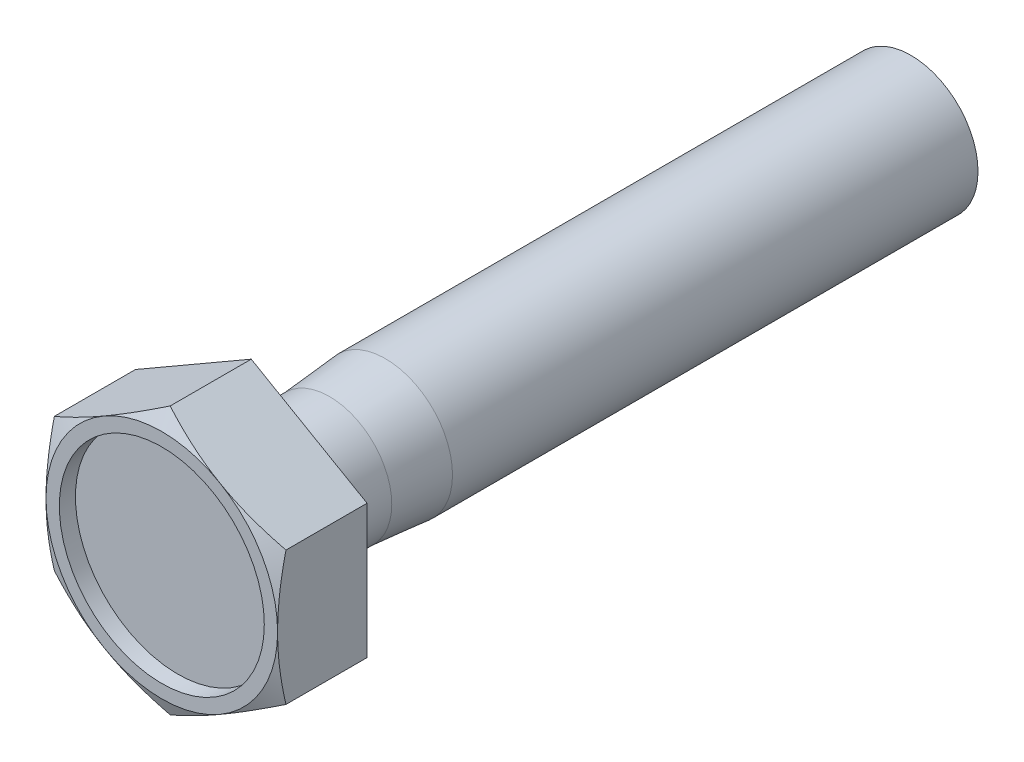
SolidWorks part; units mm, degrees
extrude "基体-拉伸" add sketch "草图3" along normal blind 2
sketch "草图3" plane through (0, 0, 0) normal (0, 0, 1) x (1, 0, 0)
  line L1 (2.5894, -1.495) -> (2.5894, 1.495)
  line L2 (2.5894, 1.495) -> (0, 2.99)
  line L3 (0, 2.99) -> (-2.5894, 1.495)
  line L4 (-2.5894, 1.495) -> (-2.5894, -1.495)
  line L5 (-2.5894, -1.495) -> (0, -2.99)
  line L6 (0, -2.99) -> (2.5894, -1.495)
  circle A0 centre (0, 0) radius 2.5894 construction
  dimension "D1" = 5.98
revolve "凸台-旋转1" add sketch "草图6"
sketch "草图6" plane through (0, 0, 0) normal (1, 0, 0) x (0, 0, -1)
  line L0 (0, 0) -> (2.3184, 0) construction
  line L2 (0, 1.3917) -> (1.75, 1.3917)
  line L3 (0, -1.495) -> (0, 1.495) construction
  line L4 (1.75, 1.3917) -> (3, 1.5)
  line L5 (3, 1.5) -> (15, 1.5)
  line L6 (15, 1.5) -> (15, 0)
  line L7 (0, 0) -> (15, 0)
  line L8 (0, 0) -> (0, 1.3917)
  dimension "D1" = 2.7835
  dimension "D2" = 3
  dimension "D3" = 1.25
  dimension "D4" = 15
  dimension "D5" = 12
cosmetic thread "螺旋线1"
revolve "切除-旋转1" cut sketch "草图7" angle 360 about L5
sketch "草图7" plane through (0, 0, 0) normal (0, 1, 0) x (1, 0, 0)
  line L0 (1.5, 15.25) -> (1.5, 14.75)
  line L1 (1.5, 14.75) -> (1.067, 15)
  line L2 (1.5, 15) -> (-1.5, 15) construction
  line L3 (1.067, 15) -> (1.5, 15.25)
  line L5 (0, 0) -> (0, 2.1791) construction
  dimension "D2" = 60
  dimension "D3" = 60
  dimension "D1" = 0.433
  dimension "D4" = 1.5
material "5.8级"
ref_plane "前视" through (0, 0, 0) normal (0, 0, 1) x (1, 0, 0)
ref_plane "上视" through (0, 0, 0) normal (0, 1, 0) x (1, 0, 0)
ref_plane "右视" through (0, 0, 0) normal (1, 0, 0) x (0, 0, -1)
sketch "尺寸草图" plane through (0, 0, 0) normal (0, 1, 0) x (1, 0, 0)
  line L0 (4.2057, 0) -> (-4.2057, 0)
  line L1 (30.1422, -1.495) -> (30.1422, 1.495)
  line L2 (30.1422, 1.495) -> (27.5527, 2.99)
  line L3 (27.5527, 2.99) -> (24.9633, 1.495)
  line L4 (24.9633, 1.495) -> (24.9633, -1.495)
  line L5 (24.9633, -1.495) -> (27.5527, -2.99)
  line L6 (27.5527, -2.99) -> (30.1422, -1.495)
  line L7 (-4.2057, 0) -> (-5.2005, 0.6605)
  line L8 (-5.2005, 0.6605) -> (-5.2005, 2)
  line L9 (-5.2005, 2) -> (-0.945, 2)
  line L10 (-0.845, 2.1) -> (-0.845, 3.75)
  line L11 (-0.845, 3.75) -> (-1.5, 5)
  line L12 (-1.5, 5) -> (-1.5, 17)
  line L13 (-1.5, 17) -> (1.5, 17)
  line L14 (1.5, 5) -> (1.5, 17)
  line L15 (0, 0) -> (0, -2.324) construction
  line L16 (0.845, 3.75) -> (1.5, 5)
  line L17 (0.845, 2.1) -> (0.845, 3.75)
  line L18 (5.2005, 2) -> (0.945, 2)
  line L19 (5.2005, 0.6605) -> (5.2005, 2)
  line L20 (4.2057, 0) -> (5.2005, 0.6605)
  circle A0 centre (27.5527, 0) radius 2.5894 construction
  circle A1 centre (27.5527, 0) radius 2.75
  arc A2 (-0.945, 2) -> (-0.845, 2.1) centre (-0.945, 2.1) ccw
  arc A3 (0.945, 2) -> (0.845, 2.1) centre (0.945, 2.1) cw
  point P26 (1.5, 17)
  point P31 (1.5, 16.5)
  point P32 (0, 12)
  dimension "s" = 5.5
sketch "草图4" plane through (0, 0, 2) normal (0, 0, 1) x (1, 0, 0)
  line L0 (-2.5894, -1.495) -> (0, -2.99) construction
  circle A0 centre (0, 0) radius 2.5894
extrude "切除-拉伸1" cut sketch "草图4" against normal blind 10 draft 65 flip side to cut
sketch "草图5" plane through (0, 0, 2) normal (0, 0, 1) x (1, 0, 0)
  circle A0 centre (0, 0) radius 2.2917
  dimension "D1" = 4.5833
extrude "切除-拉伸2" cut sketch "草图5" against normal blind 0.36
pattern_linear "阵列(线性)1" [suppressed] count 25 spacing 0.5
fillet "圆角1" radius 0.1 1 edges at (1.3917, 0, 0)
equation "\"D2@草图6\" = \"D@尺寸草图\""
equation "\"D5@草图6\" = \"b@尺寸草图\""
equation "\"D1@草图3\" = \"e@尺寸草图\""
equation "\"D1@基体-拉伸\" = \"K@尺寸草图\""
equation "\"D1@圆角1\" = \"r@尺寸草图\""
equation "\"D1@草图4\" = \"s@尺寸草图\""
equation "\"D3@草图6\" = \"x@尺寸草图\""
equation "\"D3@阵列(线性)1\" = \"P@尺寸草图\""
equation "\"D4@草图6\" = \"L@尺寸草图\""
equation "\"D1@草图5\" = \"s@尺寸草图\"*5/6"
equation "\"D1@切除-拉伸2\" = \"D1@基体-拉伸\"*0.18"
equation "\"D1@草图7\" = \"D3@阵列(线性)1\"*0.866"
equation "\"D1@草图6\" = \"D2@草图6\"-\"D1@草图7\"/2"
equation "\"D1@阵列(线性)1\" = \"D5@草图6\"/\"D3@阵列(线性)1\"+1"
equation "\"D4@草图7\" = \"D2@草图6\" / 2"
equation "\"D1@螺旋线1\" = \"D5@草图6\" + \"D3@草图6\"/2"
equation "\"D2@螺旋线1\" = \"D2@草图6\" - \"D1@草图7\"*2"
